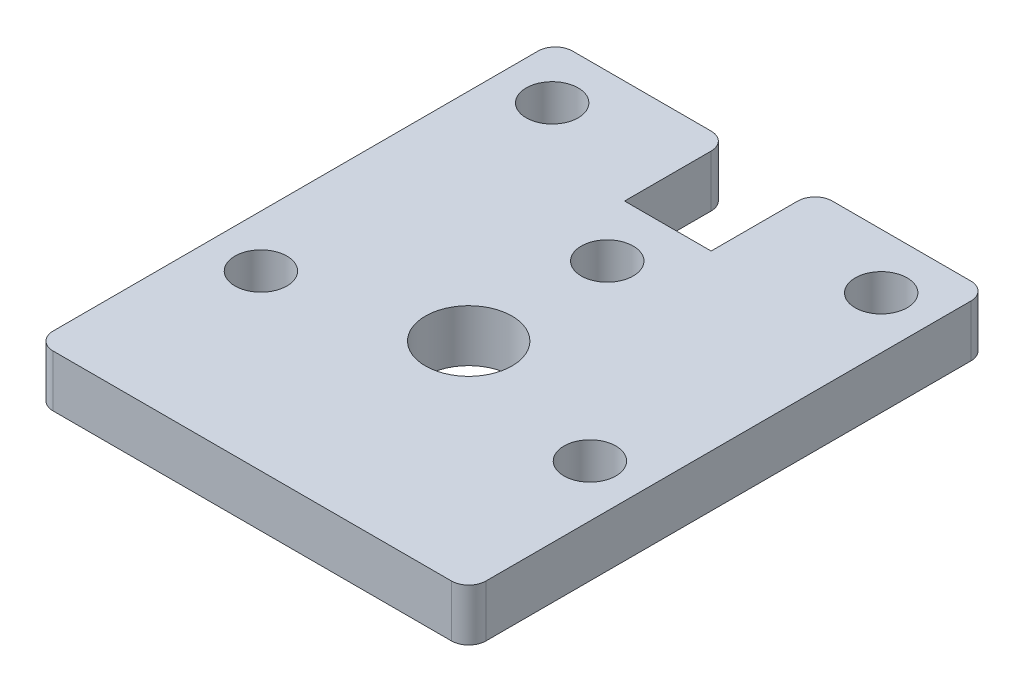
SolidWorks part; units mm, degrees
material "AISI 316 Stainless Steel Sheet (SS)"
ref_plane "Front Plane" through (0, 0, 0) normal (0, 0, 1) x (1, 0, 0)
ref_plane "Top Plane" through (0, 0, 0) normal (0, 1, 0) x (1, 0, 0)
ref_plane "Right Plane" through (0, 0, 0) normal (1, 0, 0) x (0, 0, -1)
sketch "Sketch1" plane through (0, 0, 0) normal (0, 1, 0) x (1, 0, 0)
  line L1 (0, 0) -> (25, 0)
  line L2 (0, 0) -> (0, -30)
  line L3 (0, -30) -> (25, -30)
  line L4 (25, 0) -> (25, -30)
  line L5 (5, 0) -> (20, 0) construction
  line L6 (5, 0) -> (5, -25) construction
  line L7 (5, -25) -> (20, -25) construction
  line L8 (20, 0) -> (20, -25) construction
  line L9 (7.5, -12.7) -> (17.5, -12.7) construction
  line L10 (7.5, -12.7) -> (7.5, 0) construction
  line L11 (7.5, 0) -> (17.5, 0) construction
  line L12 (17.5, -12.7) -> (17.5, 0) construction
  circle A0 centre (12.5, -3.18) radius 2.5 construction
  circle A1 centre (3, -20) radius 1.5
  circle A2 centre (22, -20) radius 1.5
  circle A3 centre (22, -3.18) radius 1.5
  circle A4 centre (3, -3.18) radius 1.5
  point P8 (12.5, 0)
  point P10 (12.5, -25)
  point P23 (12.5, -12.7)
  dimension "D2" = 5
  dimension "D8" = 3
  dimension "D1" = 25
  dimension "D3" = 3.18
  dimension "D4" = 30
  dimension "D5" = 3.18
  dimension "D6" = 3
  dimension "D7" = 3
  dimension "D9" = 15
  dimension "D10" = 3.18
  dimension "D11" = 25
  dimension "D12" = 10
  dimension "D13" = 20
  dimension "D14" = 12.7
extrude "Boss-Extrude1" add sketch "Sketch1" along normal blind 3
sketch "Sketch2" plane through (0, 3, 0) normal (0, 1, 0) x (1, 0, 0)
  line L0 (25, 0) -> (0, 0) construction
  line L1 (10, 0) -> (15, 0)
  line L2 (10, 0) -> (10, -6)
  line L3 (10, -6) -> (15, -6)
  line L4 (15, 0) -> (15, -6)
  line L6 (7.5, 0) -> (17.5, 0) construction
  line L7 (0, 0) -> (10, 0) construction
  line L8 (15, 0) -> (25, 0) construction
  line L9 (12.5, 0) -> (12.5, -17.5) construction
  line L10 (7.5, 0) -> (7.5, -12.7) construction
  line L11 (7.5, -12.7) -> (17.5, -12.7) construction
  line L12 (17.5, 0) -> (17.5, -12.7) construction
  circle A0 centre (12.5, -9.5) radius 1.5
  circle A1 centre (12.5, -17.5) radius 2.5
  point P15 (12.5, 0)
  point P20 (0, 0)
  dimension "D3" = 5
  dimension "D4" = 3.5
  dimension "D8" = 3
  dimension "D1" = 5
  dimension "D2" = 6
  dimension "D5" = 8
  dimension "D6" = 10
  dimension "D7" = 12.7
extrude "Cut-Extrude1" cut sketch "Sketch2" against normal through all
fillet "Fillet2" radius 1 6 edges at (0, 1.5, 30) (25, 1.5, 30) (0, 1.5, 0) (10, 1.5, 0) (15, 1.5, 0) (25, 1.5, 0)
